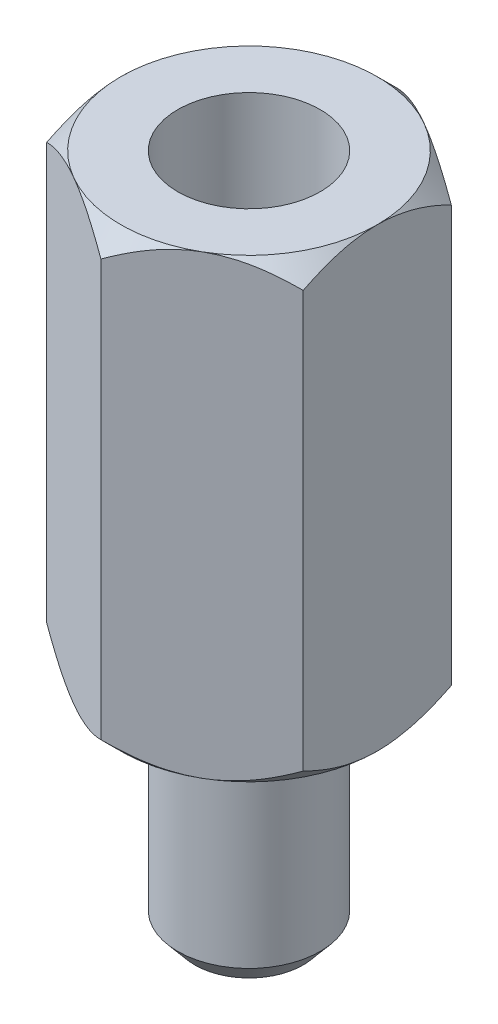
SolidWorks part; units mm, degrees
ref_plane "Front Plane" through (0, 0, 0) normal (0, 0, 1) x (1, 0, 0)
ref_plane "Top Plane" through (0, 0, 0) normal (0, 1, 0) x (1, 0, 0)
ref_plane "Right Plane" through (0, 0, 0) normal (1, 0, 0) x (0, 0, -1)
sketch "Sketch1" plane through (0, 0, 0) normal (0, 1, 0) x (1, 0, 0)
  circle A0 centre (0, 0) radius 1.25
  dimension "D1" = 2.5
extrude "Boss-Extrude1" add sketch "Sketch1" along normal blind 3.9
sketch "Sketch2" plane through (0, 3.9, 0) normal (0, 1, 0) x (1, 0, 0)
  line L1 (0, -2.5981) -> (2.25, -1.299)
  line L2 (2.25, -1.299) -> (2.25, 1.299)
  line L3 (2.25, 1.299) -> (0, 2.5981)
  line L4 (0, 2.5981) -> (-2.25, 1.299)
  line L5 (-2.25, 1.299) -> (-2.25, -1.299)
  line L6 (-2.25, -1.299) -> (0, -2.5981)
  circle A0 centre (0, 0) radius 2.25 construction
  dimension "D1" = 4.5
extrude "Boss-Extrude2" add sketch "Sketch2" along normal blind 8
sketch "Sketch3" plane through (0, 11.9, 0) normal (0, 1, 0) x (1, 0, 0)
  circle A0 centre (0, 0) radius 1.25
  dimension "D1" = 2.5
extrude "Cut-Extrude1" cut sketch "Sketch3" against normal blind 4.8
sketch "Sketch4" plane through (0, 11.9, 0) normal (0, 1, 0) x (1, 0, 0)
  circle A0 centre (0, 0) radius 2.25
extrude "Cut-Extrude2" cut sketch "Sketch4" against normal through all draft 45 flip side to cut
sketch "Sketch5" plane through (0, 3.9, 0) normal (0, -1, 0) x (1, 0, 0)
  circle A0 centre (0, 0) radius 2.25
extrude "Cut-Extrude3" cut sketch "Sketch5" against normal through all draft 45 flip side to cut
chamfer "Chamfer1" distance 0.3 angle 50 1 edges at (0, 0, 1.25)
